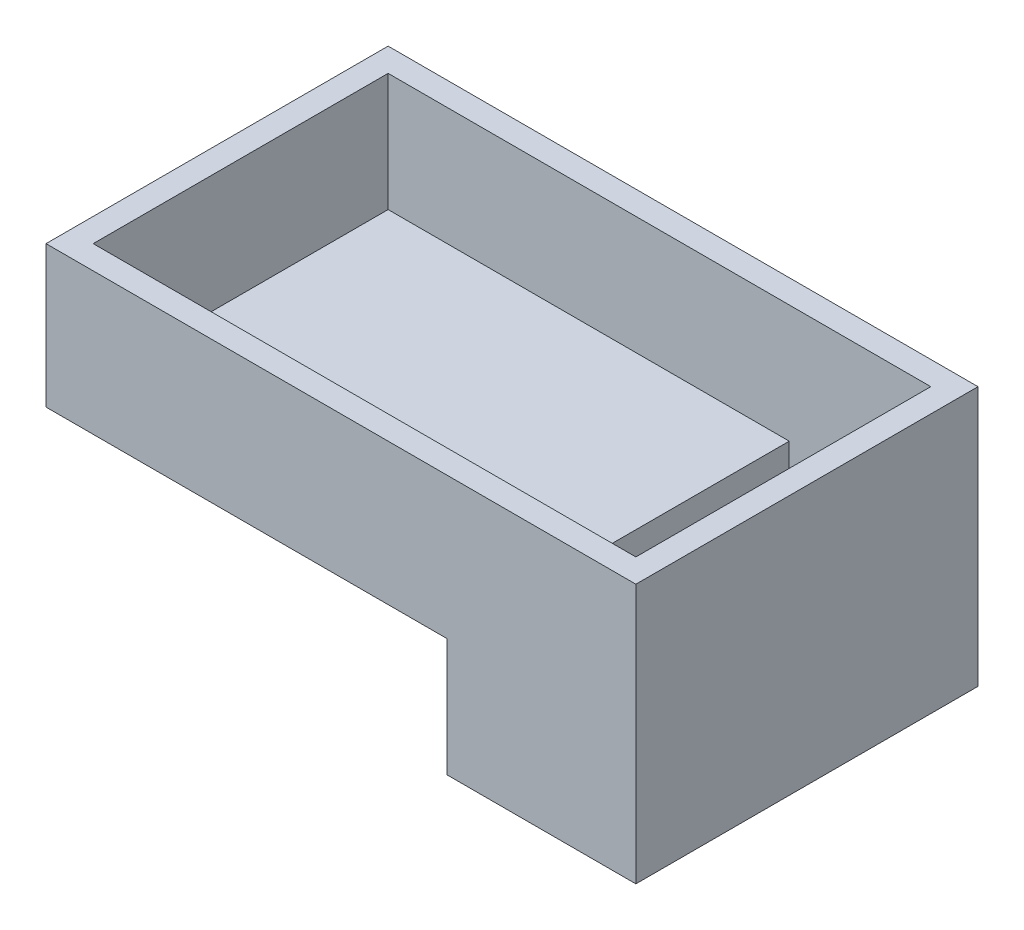
SolidWorks part; units mm, degrees
ref_plane "前视基准面" through (0, 0, 0) normal (0, 0, 1) x (1, 0, 0)
ref_plane "上视基准面" through (0, 0, 0) normal (0, 1, 0) x (1, 0, 0)
ref_plane "右视基准面" through (0, 0, 0) normal (1, 0, 0) x (0, 0, -1)
sketch "草图1" plane through (0, 0, 0) normal (0, 0, 1) x (1, 0, 0)
  line L0 (-53.922, 26.961) -> (-53.922, 20.961)
  line L1 (-53.922, 20.961) -> (-36.922, 20.961)
  line L2 (-36.922, 20.961) -> (-36.922, 15.961)
  line L3 (-36.922, 15.961) -> (-28.922, 15.961)
  line L4 (-28.922, 15.961) -> (-28.922, 26.961)
  line L5 (-28.922, 26.961) -> (-53.922, 26.961)
extrude "凸台-拉伸1" add sketch "草图1" along normal blind 1 contours L5 L0 L1 L2 L3 L4
sketch "草图2" plane through (0, 0, 1) normal (0, 0, 1) x (1, 0, 0)
  line L0 (-53.922, 26.961) -> (-52.922, 26.961)
  line L1 (-28.922, 26.961) -> (-53.922, 26.961) construction
  line L2 (-52.922, 26.961) -> (-52.922, 21.961)
  line L3 (-52.922, 21.961) -> (-35.922, 21.961)
  line L4 (-35.922, 21.961) -> (-35.922, 16.961)
  line L5 (-35.922, 16.961) -> (-29.922, 16.961)
  line L6 (-29.922, 16.961) -> (-29.922, 26.961)
  line L7 (-53.922, 26.961) -> (-53.922, 20.961)
  line L8 (-53.922, 20.961) -> (-36.922, 20.961)
  line L9 (-36.922, 20.961) -> (-36.922, 15.961)
  line L10 (-36.922, 15.961) -> (-28.922, 15.961)
  line L11 (-28.922, 15.961) -> (-28.922, 26.961)
  line L12 (-28.922, 26.961) -> (-29.922, 26.961)
extrude "凸台-拉伸2" add sketch "草图2" along normal blind 12.5 contours L12 L6 L5 L4 L3 L2 L0 L7 L8 L9 L10 L11
sketch "草图4" plane through (0, 0, 13.5) normal (0, 0, 1) x (1, 0, 0)
  line L0 (-53.922, 26.961) -> (-28.922, 26.961)
  line L1 (-28.922, 26.961) -> (-28.922, 15.961)
  line L2 (-28.922, 15.961) -> (-36.922, 15.961)
  line L3 (-36.922, 15.961) -> (-36.922, 20.961)
  line L4 (-53.922, 20.961) -> (-36.922, 20.961) construction
  line L5 (-36.922, 20.961) -> (-36.922, 15.961) construction
  line L6 (-36.922, 20.961) -> (-53.922, 20.961)
  line L7 (-53.922, 20.961) -> (-53.922, 26.961)
extrude "凸台-拉伸4" add sketch "草图4" along normal blind 1 contours L7 L0 L1 L2 L3 L6
